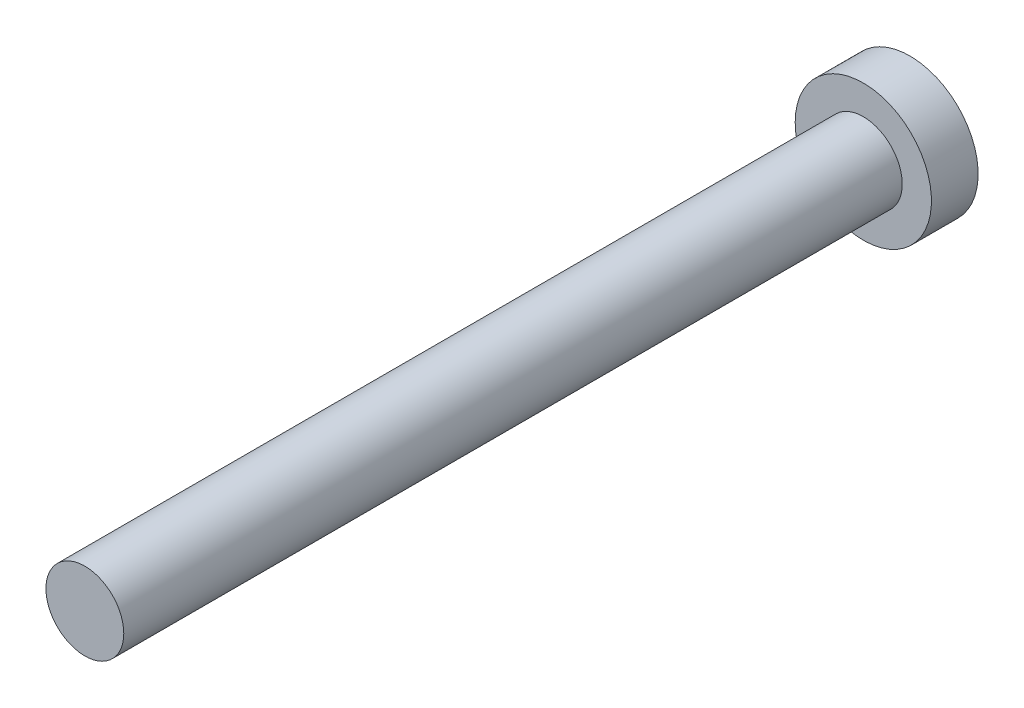
SolidWorks part; units mm, degrees
ref_plane "Front Plane" through (0, 0, 0) normal (0, 0, 1) x (1, 0, 0)
ref_plane "Top Plane" through (0, 0, 0) normal (0, 1, 0) x (1, 0, 0)
ref_plane "Right Plane" through (0, 0, 0) normal (1, 0, 0) x (0, 0, -1)
sketch "Sketch2" plane through (0, 0, 0) normal (0, 1, 0) x (1, 0, 0)
  line L0 (0, 0) -> (0, 66.8243) construction
  line L2 (0, 0) -> (-2, 0)
  line L3 (0, 0) -> (0, 40)
  line L4 (0, 40) -> (-2, 40)
  line L5 (-2, 0) -> (-2, 40)
  dimension "D1" = 40
  dimension "D2" = 4
revolve "Revolve1" add sketch "Sketch2" angle 360 about L0
sketch "Sketch3" plane through (0, 0, -40) normal (0, 0, -1) x (-1, 0, 0)
  circle A0 centre (0, 0) radius 3.5
  dimension "D1" = 7
extrude "Boss-Extrude1" add sketch "Sketch3" along normal blind 2.4
